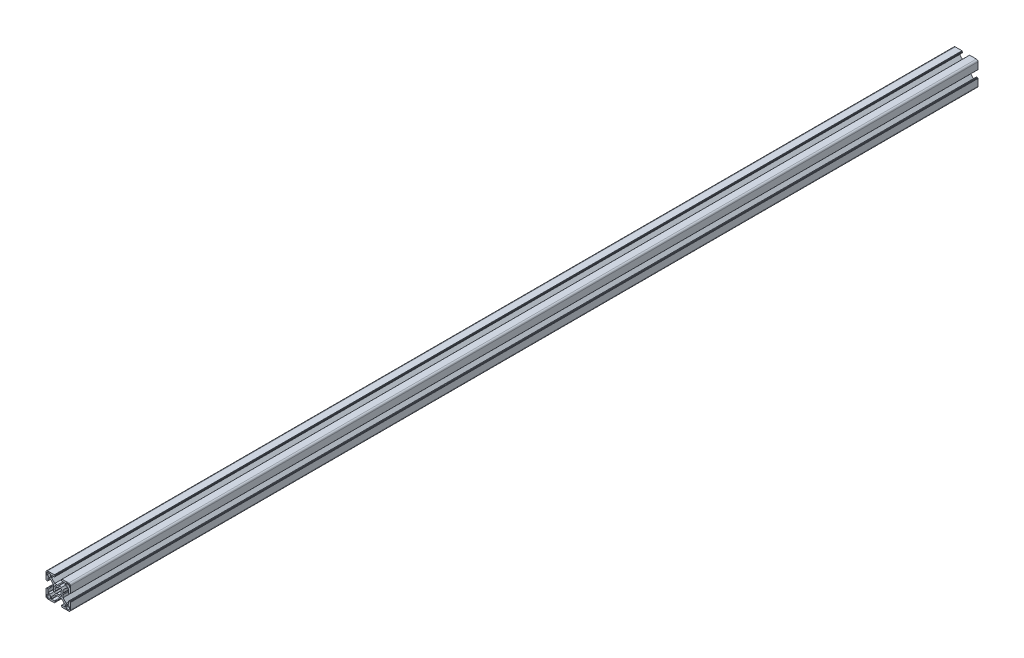
SolidWorks part; units mm, degrees
ref_plane "Płaszczyzna przednia" through (0, 0, 0) normal (0, 0, 1) x (1, 0, 0)
ref_plane "Płaszczyzna górna" through (0, 0, 0) normal (0, 1, 0) x (1, 0, 0)
ref_plane "Płaszczyzna prawa" through (0, 0, 0) normal (1, 0, 0) x (0, 0, -1)
sketch "Szkic1" plane through (0, 0, 0) normal (0, 0, 1) x (1, 0, 0)
  line L0 (109.26, 48.76) -> (107.06, 48.76)
  line L1 (106.06, 47.76) -> (106.06, 45.56)
  line L2 (107.06, 44.56) -> (109.26, 44.56)
  line L3 (110.26, 45.56) -> (110.26, 47.76)
  line L4 (94.9599, 38.3406) -> (93.4241, 39.5784)
  line L5 (92.0547, 38.2147) -> (93.2794, 36.6601)
  line L6 (93.2794, 33.4599) -> (92.0547, 31.9053)
  line L7 (93.4241, 30.5416) -> (94.9599, 31.7794)
  line L8 (98.1601, 31.7794) -> (99.6959, 30.5416)
  line L9 (101.0653, 31.9053) -> (99.8406, 33.4599)
  line L10 (99.8406, 36.6601) -> (101.0653, 38.2147)
  line L11 (99.6959, 39.5784) -> (98.1601, 38.3406)
  line L12 (83.86, 21.36) -> (86.06, 21.36)
  line L13 (87.06, 22.36) -> (87.06, 24.56)
  line L14 (86.06, 25.56) -> (83.86, 25.56)
  line L15 (82.86, 24.56) -> (82.86, 22.36)
  line L16 (110.26, 22.36) -> (110.26, 24.56)
  line L17 (109.26, 25.56) -> (107.06, 25.56)
  line L18 (106.06, 24.56) -> (106.06, 22.36)
  line L19 (86.06, 48.76) -> (83.86, 48.76)
  line L20 (82.86, 47.76) -> (82.86, 45.56)
  line L21 (83.86, 44.56) -> (86.06, 44.56)
  line L22 (87.06, 45.56) -> (87.06, 47.76)
  line L23 (107.06, 21.36) -> (109.26, 21.36)
  line L24 (96.56, 29.5751) -> (97.46, 29.06)
  line L25 (97.46, 29.06) -> (100.7645, 29.06)
  line L26 (100.7645, 29.06) -> (104.81, 25.01)
  line L27 (104.81, 25.01) -> (104.81, 22.46)
  line L28 (104.61, 22.26) -> (101.21, 22.26)
  line L29 (100.61, 21.66) -> (100.61, 20.76)
  line L30 (100.81, 20.56) -> (100.91, 20.56)
  line L31 (101.11, 20.36) -> (101.11, 20.26)
  line L32 (101.31, 20.06) -> (109.56, 20.06)
  line L33 (111.56, 22.06) -> (111.56, 30.31)
  line L34 (111.36, 30.51) -> (111.26, 30.51)
  line L35 (111.06, 30.71) -> (111.06, 30.81)
  line L36 (110.86, 31.01) -> (109.96, 31.01)
  line L37 (109.36, 30.41) -> (109.36, 27.01)
  line L38 (109.16, 26.81) -> (106.61, 26.81)
  line L39 (106.61, 26.81) -> (102.5645, 30.8555)
  line L40 (102.5645, 30.8555) -> (102.5645, 34.16)
  line L41 (102.5645, 34.16) -> (102.0449, 35.06)
  line L42 (102.0449, 35.06) -> (102.5645, 35.96)
  line L43 (102.5645, 35.96) -> (102.5645, 39.2645)
  line L44 (102.5645, 39.2645) -> (106.61, 43.31)
  line L45 (106.61, 43.31) -> (109.16, 43.31)
  line L46 (109.36, 43.11) -> (109.36, 39.71)
  line L47 (109.96, 39.11) -> (110.86, 39.11)
  line L48 (111.06, 39.31) -> (111.06, 39.41)
  line L49 (111.26, 39.61) -> (111.36, 39.61)
  line L50 (111.56, 39.81) -> (111.56, 48.06)
  line L51 (109.56, 50.06) -> (101.31, 50.06)
  line L52 (101.11, 49.86) -> (101.11, 49.76)
  line L53 (100.91, 49.56) -> (100.81, 49.56)
  line L54 (100.61, 49.36) -> (100.61, 48.46)
  line L55 (101.21, 47.86) -> (104.61, 47.86)
  line L56 (104.81, 47.66) -> (104.81, 45.11)
  line L57 (104.81, 45.11) -> (100.7645, 41.06)
  line L58 (100.7645, 41.06) -> (97.46, 41.06)
  line L59 (97.46, 41.06) -> (96.56, 40.5449)
  line L60 (96.56, 40.5449) -> (95.66, 41.06)
  line L61 (95.66, 41.06) -> (92.3555, 41.06)
  line L62 (92.3555, 41.06) -> (88.31, 45.11)
  line L63 (88.31, 45.11) -> (88.31, 47.66)
  line L64 (88.51, 47.86) -> (91.91, 47.86)
  line L65 (92.51, 48.46) -> (92.51, 49.36)
  line L66 (92.31, 49.56) -> (92.21, 49.56)
  line L67 (92.01, 49.76) -> (92.01, 49.86)
  line L68 (91.81, 50.06) -> (83.56, 50.06)
  line L69 (81.56, 48.06) -> (81.56, 39.81)
  line L70 (81.76, 39.61) -> (81.86, 39.61)
  line L71 (82.06, 39.41) -> (82.06, 39.31)
  line L72 (82.26, 39.11) -> (83.16, 39.11)
  line L73 (83.76, 39.71) -> (83.76, 43.11)
  line L74 (83.96, 43.31) -> (86.51, 43.31)
  line L75 (86.51, 43.31) -> (90.5555, 39.2645)
  line L76 (90.5555, 39.2645) -> (90.5555, 35.96)
  line L77 (90.5555, 35.96) -> (91.0751, 35.06)
  line L78 (91.0751, 35.06) -> (90.5555, 34.16)
  line L79 (90.5555, 34.16) -> (90.5555, 30.8555)
  line L80 (90.5555, 30.8555) -> (86.51, 26.81)
  line L81 (86.51, 26.81) -> (83.96, 26.81)
  line L82 (83.76, 27.01) -> (83.76, 30.41)
  line L83 (83.16, 31.01) -> (82.26, 31.01)
  line L84 (82.06, 30.81) -> (82.06, 30.71)
  line L85 (81.86, 30.51) -> (81.76, 30.51)
  line L86 (81.56, 30.31) -> (81.56, 22.06)
  line L87 (83.56, 20.06) -> (91.81, 20.06)
  line L88 (92.01, 20.26) -> (92.01, 20.36)
  line L89 (92.21, 20.56) -> (92.31, 20.56)
  line L90 (92.51, 20.76) -> (92.51, 21.66)
  line L91 (91.91, 22.26) -> (88.51, 22.26)
  line L92 (88.31, 22.46) -> (88.31, 25.01)
  line L93 (88.31, 25.01) -> (92.3555, 29.06)
  line L94 (92.3555, 29.06) -> (95.66, 29.06)
  line L95 (95.66, 29.06) -> (96.56, 29.5751)
  arc A0 (107.06, 48.76) -> (106.06, 47.76) centre (107.06, 47.76) ccw
  arc A1 (106.06, 45.56) -> (107.06, 44.56) centre (107.06, 45.56) ccw
  arc A2 (109.26, 44.56) -> (110.26, 45.56) centre (109.26, 45.56) ccw
  arc A3 (110.26, 47.76) -> (109.26, 48.76) centre (109.26, 47.76) ccw
  arc A4 (93.4241, 39.5784) -> (92.0547, 38.2147) centre (96.56, 35.06) ccw
  arc A5 (93.2794, 36.6601) -> (93.2794, 33.4599) centre (96.56, 35.06) ccw
  arc A6 (92.0547, 31.9053) -> (93.4241, 30.5416) centre (96.56, 35.06) ccw
  arc A7 (94.9599, 31.7794) -> (98.1601, 31.7794) centre (96.56, 35.06) ccw
  arc A8 (99.6959, 30.5416) -> (101.0653, 31.9053) centre (96.56, 35.06) ccw
  arc A9 (99.8406, 33.4599) -> (99.8406, 36.6601) centre (96.56, 35.06) ccw
  arc A10 (101.0653, 38.2147) -> (99.6959, 39.5784) centre (96.56, 35.06) ccw
  arc A11 (98.1601, 38.3406) -> (94.9599, 38.3406) centre (96.56, 35.06) ccw
  arc A12 (86.06, 21.36) -> (87.06, 22.36) centre (86.06, 22.36) ccw
  arc A13 (87.06, 24.56) -> (86.06, 25.56) centre (86.06, 24.56) ccw
  arc A14 (83.86, 25.56) -> (82.86, 24.56) centre (83.86, 24.56) ccw
  arc A15 (82.86, 22.36) -> (83.86, 21.36) centre (83.86, 22.36) ccw
  arc A16 (109.26, 21.36) -> (110.26, 22.36) centre (109.26, 22.36) ccw
  arc A17 (110.26, 24.56) -> (109.26, 25.56) centre (109.26, 24.56) ccw
  arc A18 (107.06, 25.56) -> (106.06, 24.56) centre (107.06, 24.56) ccw
  arc A19 (106.06, 22.36) -> (107.06, 21.36) centre (107.06, 22.36) ccw
  arc A20 (83.86, 48.76) -> (82.86, 47.76) centre (83.86, 47.76) ccw
  arc A21 (82.86, 45.56) -> (83.86, 44.56) centre (83.86, 45.56) ccw
  arc A22 (86.06, 44.56) -> (87.06, 45.56) centre (86.06, 45.56) ccw
  arc A23 (87.06, 47.76) -> (86.06, 48.76) centre (86.06, 47.76) ccw
  arc A24 (104.61, 22.26) -> (104.81, 22.46) centre (104.61, 22.46) ccw
  arc A25 (101.21, 22.26) -> (100.61, 21.66) centre (101.21, 21.66) ccw
  arc A26 (100.61, 20.76) -> (100.81, 20.56) centre (100.81, 20.76) ccw
  arc A27 (101.11, 20.36) -> (100.91, 20.56) centre (100.91, 20.36) ccw
  arc A28 (101.11, 20.26) -> (101.31, 20.06) centre (101.31, 20.26) ccw
  arc A29 (109.56, 20.06) -> (111.56, 22.06) centre (109.56, 22.06) ccw
  arc A30 (111.56, 30.31) -> (111.36, 30.51) centre (111.36, 30.31) ccw
  arc A31 (111.06, 30.71) -> (111.26, 30.51) centre (111.26, 30.71) ccw
  arc A32 (111.06, 30.81) -> (110.86, 31.01) centre (110.86, 30.81) ccw
  arc A33 (109.96, 31.01) -> (109.36, 30.41) centre (109.96, 30.41) ccw
  arc A34 (109.16, 26.81) -> (109.36, 27.01) centre (109.16, 27.01) ccw
  arc A35 (109.36, 43.11) -> (109.16, 43.31) centre (109.16, 43.11) ccw
  arc A36 (109.36, 39.71) -> (109.96, 39.11) centre (109.96, 39.71) ccw
  arc A37 (110.86, 39.11) -> (111.06, 39.31) centre (110.86, 39.31) ccw
  arc A38 (111.26, 39.61) -> (111.06, 39.41) centre (111.26, 39.41) ccw
  arc A39 (111.36, 39.61) -> (111.56, 39.81) centre (111.36, 39.81) ccw
  arc A40 (111.56, 48.06) -> (109.56, 50.06) centre (109.56, 48.06) ccw
  arc A41 (101.31, 50.06) -> (101.11, 49.86) centre (101.31, 49.86) ccw
  arc A42 (100.91, 49.56) -> (101.11, 49.76) centre (100.91, 49.76) ccw
  arc A43 (100.81, 49.56) -> (100.61, 49.36) centre (100.81, 49.36) ccw
  arc A44 (100.61, 48.46) -> (101.21, 47.86) centre (101.21, 48.46) ccw
  arc A45 (104.81, 47.66) -> (104.61, 47.86) centre (104.61, 47.66) ccw
  arc A46 (88.51, 47.86) -> (88.31, 47.66) centre (88.51, 47.66) ccw
  arc A47 (91.91, 47.86) -> (92.51, 48.46) centre (91.91, 48.46) ccw
  arc A48 (92.51, 49.36) -> (92.31, 49.56) centre (92.31, 49.36) ccw
  arc A49 (92.01, 49.76) -> (92.21, 49.56) centre (92.21, 49.76) ccw
  arc A50 (92.01, 49.86) -> (91.81, 50.06) centre (91.81, 49.86) ccw
  arc A51 (83.56, 50.06) -> (81.56, 48.06) centre (83.56, 48.06) ccw
  arc A52 (81.56, 39.81) -> (81.76, 39.61) centre (81.76, 39.81) ccw
  arc A53 (82.06, 39.41) -> (81.86, 39.61) centre (81.86, 39.41) ccw
  arc A54 (82.06, 39.31) -> (82.26, 39.11) centre (82.26, 39.31) ccw
  arc A55 (83.16, 39.11) -> (83.76, 39.71) centre (83.16, 39.71) ccw
  arc A56 (83.96, 43.31) -> (83.76, 43.11) centre (83.96, 43.11) ccw
  arc A57 (83.76, 27.01) -> (83.96, 26.81) centre (83.96, 27.01) ccw
  arc A58 (83.76, 30.41) -> (83.16, 31.01) centre (83.16, 30.41) ccw
  arc A59 (82.26, 31.01) -> (82.06, 30.81) centre (82.26, 30.81) ccw
  arc A60 (81.86, 30.51) -> (82.06, 30.71) centre (81.86, 30.71) ccw
  arc A61 (81.76, 30.51) -> (81.56, 30.31) centre (81.76, 30.31) ccw
  arc A62 (81.56, 22.06) -> (83.56, 20.06) centre (83.56, 22.06) ccw
  arc A63 (91.81, 20.06) -> (92.01, 20.26) centre (91.81, 20.26) ccw
  arc A64 (92.21, 20.56) -> (92.01, 20.36) centre (92.21, 20.36) ccw
  arc A65 (92.31, 20.56) -> (92.51, 20.76) centre (92.31, 20.76) ccw
  arc A66 (92.51, 21.66) -> (91.91, 22.26) centre (91.91, 21.66) ccw
  arc A67 (88.31, 22.46) -> (88.51, 22.26) centre (88.51, 22.46) ccw
  dimension "D1" = 3.65
  dimension "D2" = 30
  dimension "D3" = 30
  dimension "D4" = 8.1
extrude "Dodanie-wyciągnięcie1" add sketch "Szkic1" along normal blind 1120
